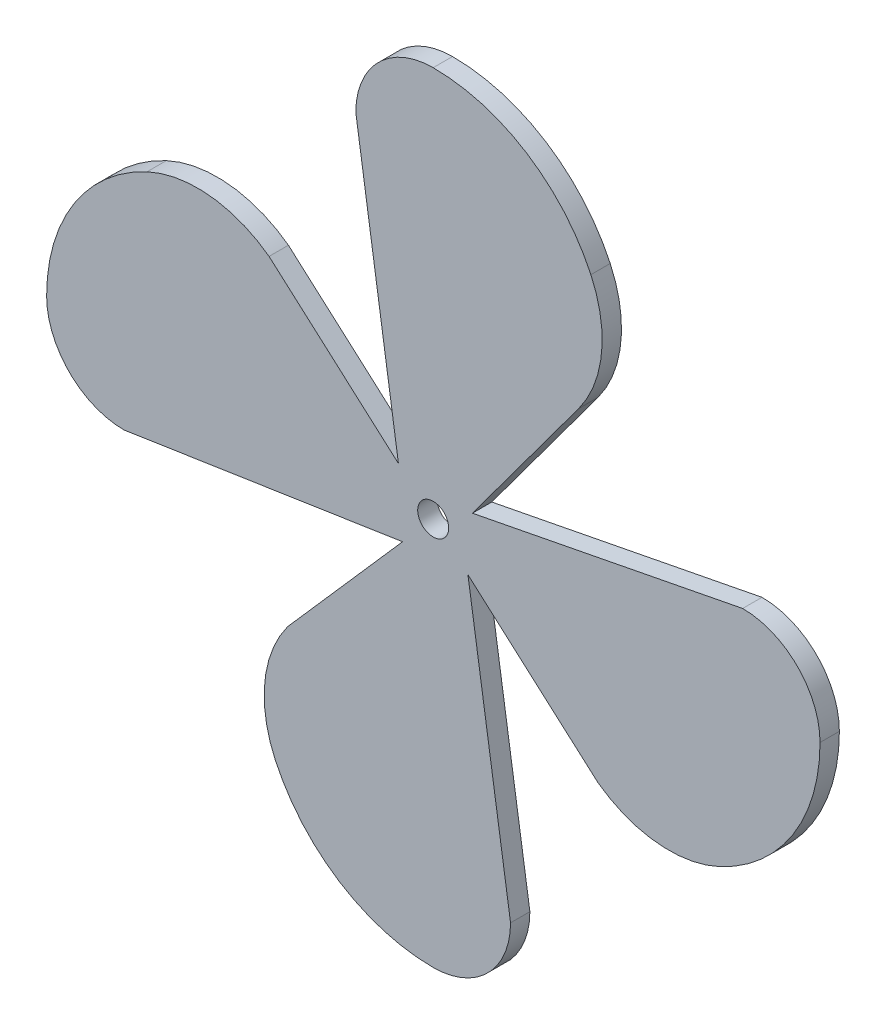
SolidWorks part; units mm, degrees
ref_plane "Front Plane" through (0, 0, 0) normal (0, 0, 1) x (1, 0, 0)
ref_plane "Top Plane" through (0, 0, 0) normal (0, 1, 0) x (1, 0, 0)
ref_plane "Right Plane" through (0, 0, 0) normal (1, 0, 0) x (0, 0, -1)
sketch "Sketch2" plane through (0, 0, 0) normal (0, 0, 1) x (1, 0, 0)
  line L0 (0, 0) -> (55, 0) construction
  line L1 (55, 0) -> (80, 0) construction
  line L2 (80, 0) -> (100, 0) construction
  line L3 (80, 0) -> (80, 68.5308) construction
  line L4 (55, 0) -> (55, -12) construction
  line L5 (55, 0) -> (42.5, 0) construction
  line L6 (42.5, 0) -> (42.5, -37.6121) construction
  line L7 (-79.9202, -20) -> (-7.9146, -9.02) construction
  line L8 (55, 0) -> (55, 25.0841) construction
  line L9 (-42.4202, 37.6121) -> (-8.9789, 7.9612) construction
  line L10 (-37.6121, -42.8654) -> (-7.9146, -9.02) construction
  line L11 (-20, 81.0583) -> (-8.9789, 7.9612) construction
  line L12 (0, 0) -> (0, 100) construction
  line L13 (0, 0) -> (0, -100) construction
  line L14 (0, 0) -> (-100, 0) construction
  line L15 (-54.9202, 0) -> (-79.9202, 0) construction
  line L16 (-79.9202, 0) -> (-99.9202, 0) construction
  line L17 (-54.9202, 0) -> (-54.9202, 12) construction
  line L18 (-54.9202, 0) -> (-42.4202, 0) construction
  line L19 (-42.4202, 0) -> (-42.4202, 37.6121) construction
  line L20 (-54.9202, 0) -> (-54.9202, -25.0841) construction
  line L21 (37.6121, 43.5583) -> (10.1482, 6.4043) construction
  line L22 (80, 20) -> (10.1482, 6.4043) construction
  line L23 (0, 56.0583) -> (0, 81.0583) construction
  line L24 (0, 81.0583) -> (0, 101.0583) construction
  line L25 (0, 56.0583) -> (12, 56.0583) construction
  line L26 (0, 56.0583) -> (0, 43.5583) construction
  line L27 (0, 43.5583) -> (37.6121, 43.5583) construction
  line L28 (0, 56.0583) -> (-25.0841, 56.0583) construction
  line L29 (42.5, -37.6121) -> (8.9863, -7.9528) construction
  line L30 (20, -80.3654) -> (8.9863, -7.9528) construction
  line L31 (0, -55.3654) -> (0, -80.3654) construction
  line L32 (0, -80.3654) -> (0, -100.3654) construction
  line L33 (0, -55.3654) -> (-12, -55.3654) construction
  line L34 (0, -55.3654) -> (0, -42.8654) construction
  line L35 (0, -42.8654) -> (-37.6121, -42.8654) construction
  line L36 (0, -55.3654) -> (25.0841, -55.3654) construction
  line L37 (-20, 81.0583) -> (-8.9789, 7.9612)
  line L38 (10.1482, 6.4043) -> (37.6121, 43.5583)
  line L39 (10.1482, 6.4043) -> (80, 20)
  line L40 (8.9863, -7.9528) -> (42.5, -37.6121)
  line L41 (20, -80.3654) -> (8.9863, -7.9528)
  line L42 (-37.6121, -42.8654) -> (-7.9146, -9.02)
  line L43 (-79.9202, -20) -> (-7.9146, -9.02)
  line L44 (-42.4202, 37.6121) -> (-8.9789, 7.9612)
  circle A0 centre (0, 0) radius 4
  circle A1 centre (0, 0) radius 12
  arc A2 (100, 0) -> (80, 20) centre (80, 0) ccw
  arc A3 (74.0515, -40.7681) -> (100, 0) centre (55, 0) ccw
  arc A5 (42.5, -37.6121) -> (74.0515, -40.7681) centre (60.9271, -12.6834) ccw
  arc A6 (-99.9202, 0) -> (-79.9202, -20) centre (-79.9202, 0) ccw
  arc A7 (-73.9716, 40.7681) -> (-99.9202, 0) centre (-54.9202, 0) ccw
  arc A8 (-42.4202, 37.6121) -> (-73.9716, 40.7681) centre (-60.8473, 12.6834) ccw
  arc A9 (0, 101.0583) -> (-20, 81.0583) centre (0, 81.0583) ccw
  arc A10 (40.7681, 75.1097) -> (0, 101.0583) centre (0, 56.0583) ccw
  arc A11 (37.6121, 43.5583) -> (40.7681, 75.1097) centre (12.6834, 61.9854) ccw
  arc A12 (0, -100.3654) -> (20, -80.3654) centre (0, -80.3654) ccw
  arc A13 (-40.7681, -74.4168) -> (0, -100.3654) centre (0, -55.3654) ccw
  arc A14 (-37.6121, -42.8654) -> (-40.7681, -74.4168) centre (-12.6834, -61.2925) ccw
extrude "Boss-Extrude1" add sketch "Sketch2" along normal blind 5 contours L38 A11 A10 A9 L37 A1 | L44 A8 A7 A6 L43 A1 | L40 A5 A3 A2 L39 A1 | L42 A14 A13 A12 L41 A1 | A1 A0
